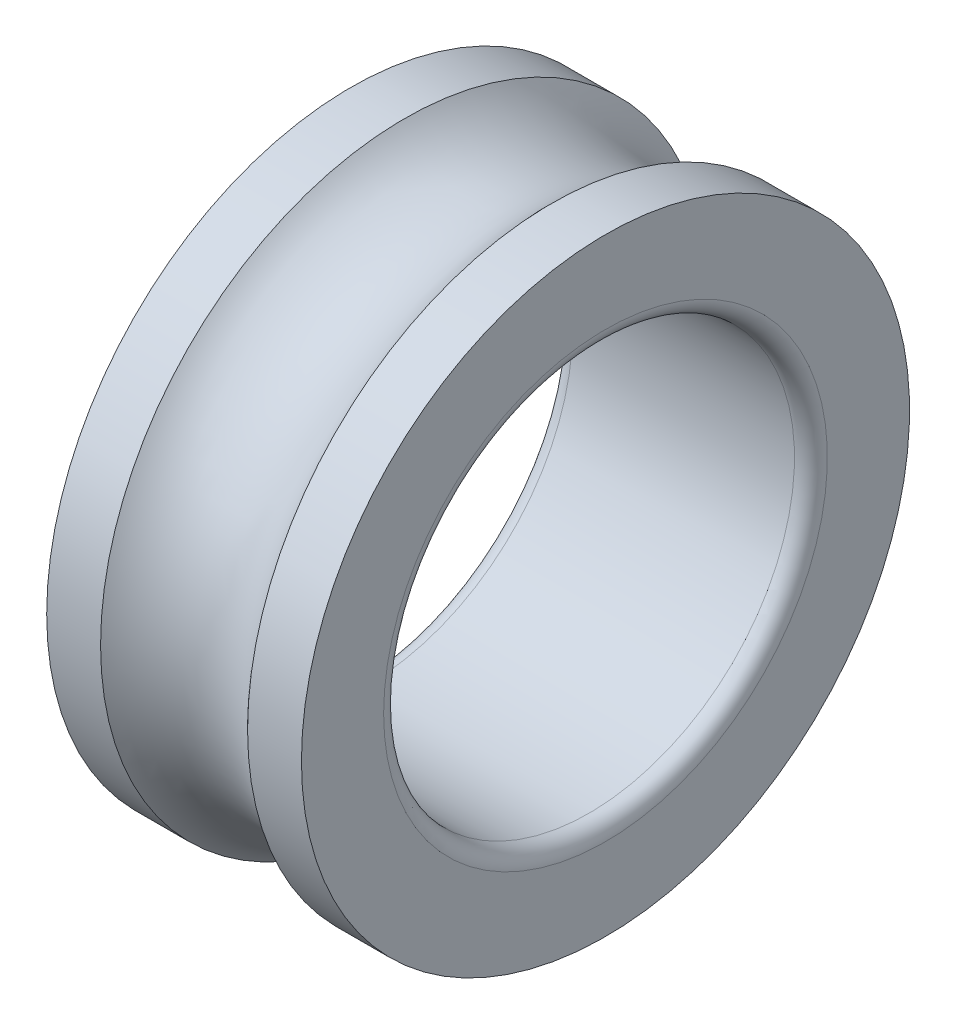
SolidWorks part; units mm, degrees
ref_plane "前视基准面" through (0, 0, 0) normal (0, 0, 1) x (1, 0, 0)
ref_plane "上视基准面" through (0, 0, 0) normal (0, 1, 0) x (1, 0, 0)
ref_plane "右视基准面" through (0, 0, 0) normal (1, 0, 0) x (0, 0, -1)
sketch "草图1" plane through (0, 0, 0) normal (0, 0, 1) x (1, 0, 0)
  line L0 (0, 0) -> (0, 31) construction
  line L1 (0, 31) -> (0, 0) construction
  line L2 (0, 0) -> (29.0599, 0) construction
  line L3 (-15.5, 37) -> (-8.9443, 37)
  line L5 (-15.5, 37) -> (-15.5, 25)
  line L6 (-15.5, 25) -> (15.5, 25)
  line L7 (15.5, 37) -> (15.5, 25)
  line L8 (-15.5, 37) -> (15.5, 25) construction
  line L9 (-15.5, 25) -> (15.5, 37) construction
  line L10 (8.9443, 37) -> (15.5, 37)
  arc A0 (-8.9443, 37) -> (8.9443, 37) centre (0, 45) ccw
  dimension "D1" = 12
  dimension "D2" = 8
  dimension "D3" = 31
  dimension "D4" = 25
  dimension "D5" = 37
revolve "旋转1" add sketch "草图1" angle 360 about L2
fillet "圆角1" radius 2 2 edges at (-15.5, 0, 25) (15.5, 0, 25)
scale "缩放比例1" scale about centroid uniform scaling yes scale factor 0.338462
scale "缩放比例2" scale about centroid uniform scaling yes scale factor 0.5
